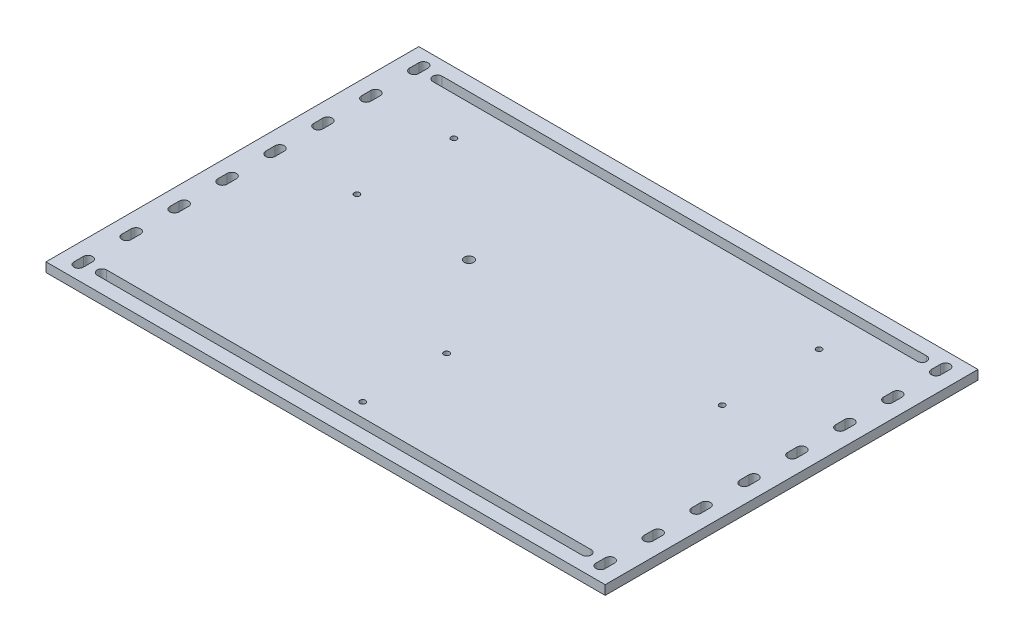
SolidWorks part; units mm, degrees
ref_plane "前基準面" through (0, 0, 0) normal (0, 0, 1) x (1, 0, 0)
ref_plane "上基準面" through (0, 0, 0) normal (0, 1, 0) x (1, 0, 0)
ref_plane "右基準面" through (0, 0, 0) normal (1, 0, 0) x (0, 0, -1)
sketch "草圖1" plane through (0, 0, 0) normal (0, 1, 0) x (1, 0, 0)
  line L0 (-130, 97.2315) -> (-150, 97.2315) construction
  line L1 (-150, 100) -> (150, 100)
  line L2 (-150, 100) -> (-150, -100)
  line L3 (-150, -100) -> (150, -100)
  line L4 (150, 100) -> (150, -100)
  line L5 (0, 100) -> (0, -100) construction
  line L6 (-150, 0) -> (150, 0) construction
  line L7 (-150, 100) -> (-130, 100) construction
  line L8 (150, -90) -> (-150, -90) construction
  line L9 (-150, 100) -> (-150, -100) construction
  line L10 (-150, -100) -> (-130, -100) construction
  line L11 (-130, 100) -> (-130, -100) construction
  line L12 (-142.25, 100) -> (-137.75, 100) construction
  line L13 (-142.25, 100) -> (-142.25, -100) construction
  line L14 (-142.25, -100) -> (-137.75, -100) construction
  line L15 (-137.75, 100) -> (-137.75, -100) construction
  line L16 (-140, 99.6012) -> (-140, 93.2772) construction
  line L17 (-140, 92.5) -> (-140, 87.5) construction
  line L18 (-137.5, 92.5) -> (-137.5, 87.5)
  line L19 (-142.5, 92.5) -> (-142.5, 87.5)
  line L20 (-140, 66.7857) -> (-140, 61.7857) construction
  line L21 (-137.5, 66.7857) -> (-137.5, 61.7857)
  line L22 (-142.5, 66.7857) -> (-142.5, 61.7857)
  line L23 (-140, 41.0714) -> (-140, 36.0714) construction
  line L24 (-137.5, 41.0714) -> (-137.5, 36.0714)
  line L25 (-142.5, 41.0714) -> (-142.5, 36.0714)
  line L26 (-140, 15.3571) -> (-140, 10.3571) construction
  line L27 (-137.5, 15.3571) -> (-137.5, 10.3571)
  line L28 (-142.5, 15.3571) -> (-142.5, 10.3571)
  line L29 (-140, -10.3571) -> (-140, -15.3571) construction
  line L30 (-137.5, -10.3571) -> (-137.5, -15.3571)
  line L31 (-142.5, -10.3571) -> (-142.5, -15.3571)
  line L32 (-140, -36.0714) -> (-140, -41.0714) construction
  line L33 (-137.5, -36.0714) -> (-137.5, -41.0714)
  line L34 (-142.5, -36.0714) -> (-142.5, -41.0714)
  line L35 (-140, -61.7857) -> (-140, -66.7857) construction
  line L36 (-137.5, -61.7857) -> (-137.5, -66.7857)
  line L37 (-142.5, -61.7857) -> (-142.5, -66.7857)
  line L38 (-140, -87.5) -> (-140, -92.5) construction
  line L39 (-137.5, -87.5) -> (-137.5, -92.5)
  line L40 (-142.5, -87.5) -> (-142.5, -92.5)
  line L41 (140, 92.5) -> (140, 87.5) construction
  line L44 (137.5, 92.5) -> (137.5, 87.5)
  line L47 (142.5, 92.5) -> (142.5, 87.5)
  line L50 (140, 66.7857) -> (140, 61.7857) construction
  line L53 (137.5, 66.7857) -> (137.5, 61.7857)
  line L56 (142.5, 66.7857) -> (142.5, 61.7857)
  line L59 (140, 41.0714) -> (140, 36.0714) construction
  line L62 (137.5, 41.0714) -> (137.5, 36.0714)
  line L65 (-150, -100) -> (150, -100) construction
  line L66 (-150, -100) -> (-150, -80) construction
  line L67 (-150, -80) -> (150, -80) construction
  line L68 (150, -100) -> (150, -80) construction
  line L69 (109.7962, -80) -> (109.7962, -100) construction
  line L70 (-130, -90) -> (130, -90) construction
  line L71 (-130, -87.5) -> (130, -87.5)
  line L72 (-130, -92.5) -> (130, -92.5)
  line L73 (-130, 90) -> (130, 90) construction
  line L74 (-130, 92.5) -> (130, 92.5)
  line L75 (-130, 87.5) -> (130, 87.5)
  line L76 (142.5, 41.0714) -> (142.5, 36.0714)
  line L77 (140, 15.3571) -> (140, 10.3571) construction
  line L78 (137.5, 15.3571) -> (137.5, 10.3571)
  line L79 (142.5, 15.3571) -> (142.5, 10.3571)
  line L80 (140, -10.3571) -> (140, -15.3571) construction
  line L81 (137.5, -10.3571) -> (137.5, -15.3571)
  line L82 (142.5, -10.3571) -> (142.5, -15.3571)
  line L83 (140, -36.0714) -> (140, -41.0714) construction
  line L84 (137.5, -36.0714) -> (137.5, -41.0714)
  line L85 (142.5, -36.0714) -> (142.5, -41.0714)
  line L86 (140, -61.7857) -> (140, -66.7857) construction
  line L87 (137.5, -61.7857) -> (137.5, -66.7857)
  line L88 (142.5, -61.7857) -> (142.5, -66.7857)
  line L89 (140, -87.5) -> (140, -92.5) construction
  line L90 (137.5, -87.5) -> (137.5, -92.5)
  line L91 (142.5, -87.5) -> (142.5, -92.5)
  line L92 (134.459, 100) -> (134.459, 80) construction
  line L93 (-150, 100) -> (150, 100) construction
  line L94 (-150, 100) -> (-150, 80) construction
  line L95 (-150, 80) -> (150, 80) construction
  line L96 (150, 100) -> (150, 80) construction
  arc A9 (-137.5, 92.5) -> (-142.5, 92.5) centre (-140, 92.5) ccw
  arc A10 (-142.5, 87.5) -> (-137.5, 87.5) centre (-140, 87.5) ccw
  arc A11 (-137.5, 66.7857) -> (-142.5, 66.7857) centre (-140, 66.7857) ccw
  arc A12 (-142.5, 61.7857) -> (-137.5, 61.7857) centre (-140, 61.7857) ccw
  arc A13 (-137.5, 41.0714) -> (-142.5, 41.0714) centre (-140, 41.0714) ccw
  arc A14 (-142.5, 36.0714) -> (-137.5, 36.0714) centre (-140, 36.0714) ccw
  arc A15 (-137.5, 15.3571) -> (-142.5, 15.3571) centre (-140, 15.3571) ccw
  arc A16 (-142.5, 10.3571) -> (-137.5, 10.3571) centre (-140, 10.3571) ccw
  arc A17 (-137.5, -10.3571) -> (-142.5, -10.3571) centre (-140, -10.3571) ccw
  arc A18 (-142.5, -15.3571) -> (-137.5, -15.3571) centre (-140, -15.3571) ccw
  arc A19 (-137.5, -36.0714) -> (-142.5, -36.0714) centre (-140, -36.0714) ccw
  arc A20 (-142.5, -41.0714) -> (-137.5, -41.0714) centre (-140, -41.0714) ccw
  arc A21 (-137.5, -61.7857) -> (-142.5, -61.7857) centre (-140, -61.7857) ccw
  arc A22 (-142.5, -66.7857) -> (-137.5, -66.7857) centre (-140, -66.7857) ccw
  arc A23 (-137.5, -87.5) -> (-142.5, -87.5) centre (-140, -87.5) ccw
  arc A24 (-142.5, -92.5) -> (-137.5, -92.5) centre (-140, -92.5) ccw
  arc A41 (-130, -87.5) -> (-130, -92.5) centre (-130, -90) ccw
  arc A42 (130, -92.5) -> (130, -87.5) centre (130, -90) ccw
  arc A43 (-130, 92.5) -> (-130, 87.5) centre (-130, 90) ccw
  arc A44 (130, 87.5) -> (130, 92.5) centre (130, 90) ccw
  arc A45 (137.5, 92.5) -> (142.5, 92.5) centre (140, 92.5) cw
  arc A46 (142.5, 87.5) -> (137.5, 87.5) centre (140, 87.5) cw
  arc A47 (137.5, 66.7857) -> (142.5, 66.7857) centre (140, 66.7857) cw
  arc A48 (142.5, 61.7857) -> (137.5, 61.7857) centre (140, 61.7857) cw
  arc A49 (137.5, 41.0714) -> (142.5, 41.0714) centre (140, 41.0714) cw
  arc A50 (142.5, 36.0714) -> (137.5, 36.0714) centre (140, 36.0714) cw
  arc A51 (137.5, 15.3571) -> (142.5, 15.3571) centre (140, 15.3571) cw
  arc A52 (142.5, 10.3571) -> (137.5, 10.3571) centre (140, 10.3571) cw
  arc A53 (137.5, -10.3571) -> (142.5, -10.3571) centre (140, -10.3571) cw
  arc A54 (142.5, -15.3571) -> (137.5, -15.3571) centre (140, -15.3571) cw
  arc A55 (137.5, -36.0714) -> (142.5, -36.0714) centre (140, -36.0714) cw
  arc A56 (142.5, -41.0714) -> (137.5, -41.0714) centre (140, -41.0714) cw
  arc A57 (137.5, -61.7857) -> (142.5, -61.7857) centre (140, -61.7857) cw
  arc A58 (142.5, -66.7857) -> (137.5, -66.7857) centre (140, -66.7857) cw
  arc A59 (137.5, -87.5) -> (142.5, -87.5) centre (140, -87.5) cw
  arc A60 (142.5, -92.5) -> (137.5, -92.5) centre (140, -92.5) cw
  point P6 (0, 0)
  point P17 (109.7962, -90)
  point P18 (0, -90)
  point P33 (-140, 97.2315)
  point P35 (-140, 90)
  point P42 (-137.5, 90)
  point P43 (-140, 64.2857)
  point P51 (-140, 38.5714)
  point P58 (-140, 12.8571)
  point P65 (-140, -12.8571)
  point P69 (0, 90)
  point P75 (-140, -38.5714)
  point P82 (-140, -64.2857)
  point P89 (-140, -90)
  point P98 (134.459, 90)
  point P107 (140, 90)
  point P114 (140, 64.2857)
  point P121 (140, 38.5714)
  point P128 (140, 12.8571)
  point P135 (140, -12.8571)
  point P142 (140, -38.5714)
  point P149 (140, -64.2857)
  point P163 (140, -90)
  dimension "D3" = 300
  dimension "D5" = 5
  dimension "D8" = 260
  dimension "D2" = 200
  dimension "D4" = 20
  dimension "D6" = 260
  dimension "D7" = 5
  dimension "D9" = 20
  dimension "D10" = 4.5
  dimension "D11" = 5
  dimension "D12" = 5
  dimension "D13" = 10
  dimension "D15" = 10
  dimension "D16" = 20
  dimension "D17" = 200
  dimension "D14" = 8
extrude "填料-伸長1" add sketch "草圖1" along normal blind 5
sketch "草圖2" plane through (0, 5, 0) normal (0, 1, 0) x (1, 0, 0)
  line L0 (0, 116.4556) -> (0, -113.9778) construction
  line L1 (110, 60) -> (25, 60) construction
  line L2 (-67.5, 102.5) -> (-67.5, 17.5) construction
  line L3 (-110, 60) -> (-25, 60) construction
  line L4 (67.5, 102.5) -> (67.5, 17.5) construction
  line L10 (7.5, -60.5789) -> (-7.5, -60.5789) construction
  line L15 (7.5, -60.5789) -> (7.5, 9.4211) construction
  line L16 (7.5, 9.4211) -> (-7.5, 9.4211) construction
  line L17 (-7.5, -60.5789) -> (-7.5, 9.4211) construction
  line L20 (-7.5, 9.4211) -> (7.5, 9.4211) construction
  line L30 (150, 100) -> (-150, 100) construction
  line L31 (-36, 26.9211) -> (36, 26.9211)
  line L32 (-36, 26.9211) -> (-36, -53.0789)
  line L33 (-36, -53.0789) -> (36, -53.0789)
  line L34 (36, 26.9211) -> (36, -53.0789)
  line L36 (36, -53.0789) -> (-36, -53.0789) construction
  line L37 (36, -53.0789) -> (36, 16.9211) construction
  line L38 (36, 16.9211) -> (-36, 16.9211) construction
  line L39 (-36, -53.0789) -> (-36, 16.9211) construction
  line L52 (144, 10.7857) -> (94, 10.7857)
  line L53 (-144, 70.7857) -> (-94, 70.7857)
  line L54 (-144, 70.7857) -> (-144, 10.7857)
  line L55 (-144, 10.7857) -> (-94, 10.7857)
  line L56 (-94, 70.7857) -> (-94, 10.7857)
  line L57 (94, 70.7857) -> (94, 10.7857)
  line L58 (144, 70.7857) -> (94, 70.7857)
  line L59 (144, 70.7857) -> (144, 10.7857)
  line L60 (-7.5, -13.0789) -> (7.5, -13.0789)
  line L61 (-7.5, -13.0789) -> (-7.5, -38.0789)
  line L62 (-7.5, -38.0789) -> (7.5, -38.0789)
  line L63 (7.5, -13.0789) -> (7.5, -38.0789)
  line L68 (-7.5, -22.5789) -> (7.5, -22.5789) construction
  line L69 (-7.5, -22.5789) -> (-7.5, -92.5789) construction
  line L70 (-7.5, -92.5789) -> (7.5, -92.5789) construction
  line L71 (7.5, -22.5789) -> (7.5, -92.5789) construction
  line L75 (240, -187.4371) -> (-240, -187.4371)
  line L76 (240, -187.4371) -> (240, -107.4371)
  line L77 (240, -107.4371) -> (-240, -107.4371)
  line L78 (-240, -187.4371) -> (-240, -107.4371)
  line L79 (35, -107.4371) -> (-35, -107.4371)
  line L80 (35, -107.4371) -> (35, -187.4371)
  line L81 (35, -187.4371) -> (-35, -187.4371)
  line L82 (-35, -107.4371) -> (-35, -187.4371)
  line L83 (0, -187.4371) -> (0, -107.4371) construction
  line L84 (35, -147.4371) -> (-35, -147.4371) construction
  circle A0 centre (-67.5, 60) radius 42.5
  circle A1 centre (-67.5, 60) radius 22.1
  circle A2 centre (-82, 60) radius 2
  circle A3 centre (-53, 60) radius 2
  circle A4 centre (53, 60) radius 2
  circle A5 centre (82, 60) radius 2
  circle A6 centre (67.5, 60) radius 22.1
  circle A7 centre (67.5, 60) radius 42.5
  circle A11 centre (0, -48.0789) radius 1.25 construction
  circle A12 centre (0, 21.9211) radius 35 construction
  circle A13 centre (0, -3.0789) radius 1.25 construction
  circle A24 centre (-140, 66.7857) radius 1.5
  circle A25 centre (-98, 66.7857) radius 1.5
  circle A26 centre (-140, 14.7857) radius 1.5
  circle A27 centre (-98, 14.7857) radius 1.5
  arc A28 (-137.5, 66.7857) -> (-142.5, 66.7857) centre (-140, 66.7857) ccw construction
  circle A29 centre (140, 14.7857) radius 1.5
  circle A30 centre (140, 66.7857) radius 1.5
  circle A34 centre (0, -35.0789) radius 1.5
  circle A35 centre (0, -80.0789) radius 1.5
  point P15 (0, -13.0789)
  point P29 (0, 0)
  point P39 (0, 0)
  point P41 (-37.5, -45.5789)
  point P43 (0, 26.9211)
  point P46 (-7.5, -25.5789)
  point P50 (0, 0)
  point P51 (0, 0)
  point P57 (-7.5, -25.5789)
  point P61 (0, 0)
  point P62 (0, 0)
  point P63 (0, 0)
  point P79 (0, 0)
  point P85 (-96.5, 66.7857)
  point P90 (-141.5, 66.7857)
  point P91 (-140, 13.2857)
  point P92 (-140, 68.2857)
  point P101 (98, 14.7857)
  point P116 (0, -60.5789)
  point P130 (0, -92.5789)
  point P131 (0, 0)
  point P142 (0, -187.4371)
  point P143 (0, -147.4371)
  point P147 (0, -157.0002)
  point P148 (0, -147.4371)
  point P149 (-37.5, 14.4211)
  dimension "D1" = 85
  dimension "D2" = 44.2
  dimension "D4" = 4
  dimension "D8" = 40
  dimension "D10" = 40
  dimension "D7" = 2
  dimension "D16" = 70
  dimension "D13" = 2.5
  dimension "D22" = 60
  dimension "D24" = 45
  dimension "D25" = 3
  dimension "D36" = 45
  dimension "D39" = 3
  dimension "D3" = 29
  dimension "D5" = 50
  dimension "D6" = 12.5
  dimension "D9" = 25
  dimension "D11" = 70
  dimension "D12" = 70
  dimension "D14" = 80
  dimension "D15" = 72
  dimension "D20" = 45
  dimension "D23" = 50
  dimension "D26" = 4
  dimension "D27" = 4
  dimension "D28" = 2
  dimension "D29" = 55
  dimension "D31" = 15
  dimension "D34" = 70
  dimension "D35" = 15
  dimension "D37" = 12.5
  dimension "D38" = 32
  dimension "D43" = 80
  dimension "D44" = 480
  dimension "D45" = 70
sketch "草圖3" plane through (0, 5, 0) normal (0, 1, 0) x (1, 0, 0)
  line L0 (0, 200116.4556) -> (0, -200113.9778) construction
  line L1 (0, 200116.4556) -> (0, -200113.9778) construction
  circle A0 centre (0, -80.0789) radius 1.5 construction
  circle A1 centre (0, -80.0789) radius 1.5
  circle A2 centre (0, -35.0789) radius 1.5 construction
  circle A3 centre (0, -35.0789) radius 1.5
  circle A4 centre (-98, 14.7857) radius 1.5 construction
  circle A5 centre (-98, 14.7857) radius 1.5
  circle A6 centre (-98, 66.7857) radius 1.5 construction
  circle A7 centre (-98, 66.7857) radius 1.5
  circle A8 centre (98, 14.7857) radius 1.5
  circle A9 centre (98, 66.7857) radius 1.5
  circle A10 centre (-37.5, 14.4211) radius 2.5
  dimension "D2" = 5
  dimension "D1" = 45
extrude "除料-伸長1" cut sketch "草圖3" against normal through all
